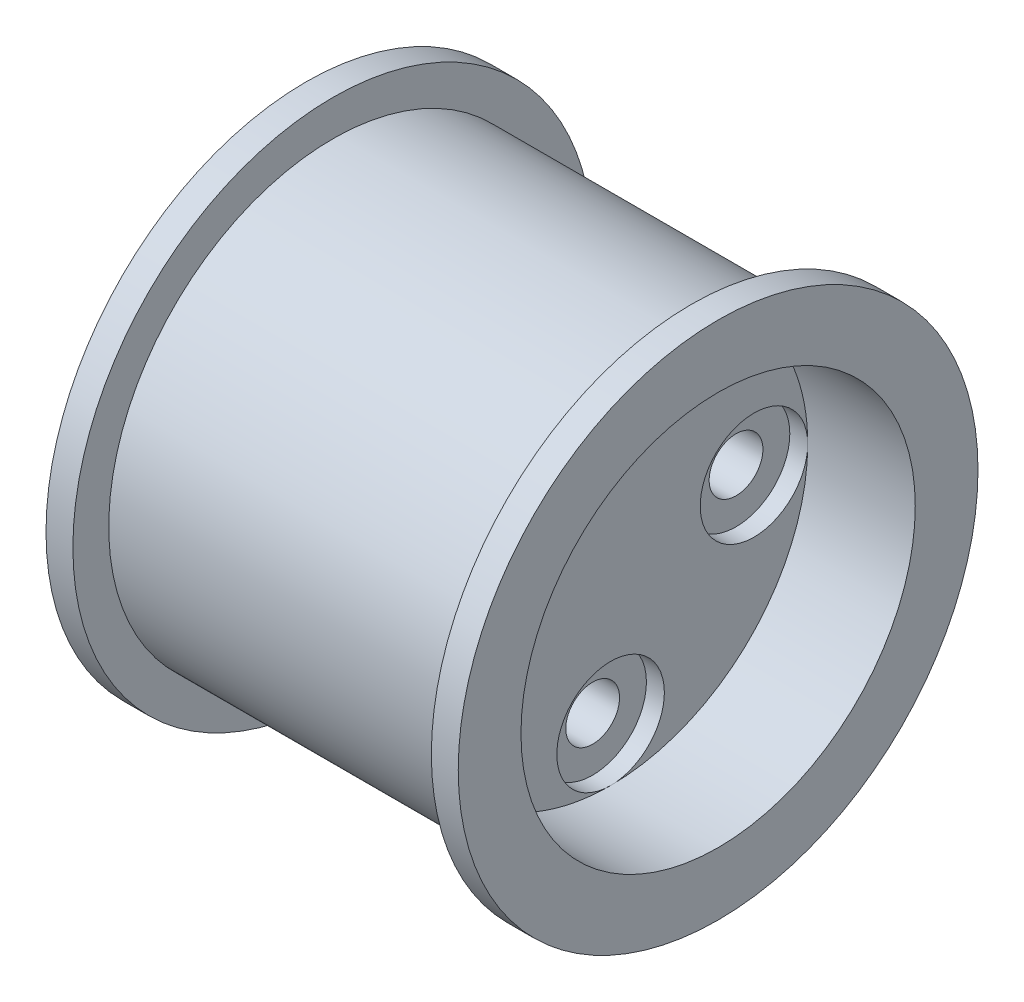
SolidWorks part; units mm, degrees
ref_plane "Front Plane" through (0, 0, 0) normal (0, 0, 1) x (1, 0, 0)
ref_plane "Top Plane" through (0, 0, 0) normal (0, 1, 0) x (1, 0, 0)
ref_plane "Right Plane" through (0, 0, 0) normal (1, 0, 0) x (0, 0, -1)
sketch "Sketch1" plane through (0, 0, 0) normal (1, 0, 0) x (0, 0, -1)
  circle A0 centre (0, 0) radius 14.5
  dimension "D1" = 29
extrude "Boss-Extrude1" add sketch "Sketch1" along normal blind 1.5
sketch "Sketch2" plane through (1.5, 0, 0) normal (1, 0, 0) x (0, 0, -1)
  circle A0 centre (0, 0) radius 12.5
  dimension "D1" = 25
extrude "Boss-Extrude2" add sketch "Sketch2" along normal blind 20
sketch "Sketch3" plane through (21.5, 0, 0) normal (1, 0, 0) x (0, 0, -1)
  circle A0 centre (0, 0) radius 14.5
extrude "Boss-Extrude3" add sketch "Sketch3" along normal blind 1.5
sketch "Sketch4" plane through (23, 0, 0) normal (1, 0, 0) x (0, 0, -1)
  circle A0 centre (0, 0) radius 11
  dimension "D1" = 22
extrude "Cut-Extrude1" cut sketch "Sketch4" against normal blind 6
sketch "Sketch5" plane through (17, 0, 0) normal (1, 0, 0) x (0, 0, -1)
  circle A0 centre (0, 8) radius 1.5
  circle A1 centre (8, 0) radius 1.5
  circle A2 centre (0, -8) radius 1.5
  circle A3 centre (-8, 0) radius 1.5
  dimension "D1" = 3
  dimension "D2" = 16
  dimension "D3" = 16
  dimension "D4" = 8
  dimension "D5" = 8
extrude "Cut-Extrude2" cut sketch "Sketch5" against normal up to surface (17 mm away) up to face at (0, 0, -14.5)
sketch "Sketch6" plane through (17, 0, 0) normal (1, 0, 0) x (0, 0, -1)
  circle A0 centre (0, 8) radius 3
  circle A1 centre (8, 0) radius 3
  circle A2 centre (0, -8) radius 3
  circle A3 centre (-8, 0) radius 3
  dimension "D1" = 6
extrude "Cut-Extrude3" cut sketch "Sketch6" against normal blind 1
